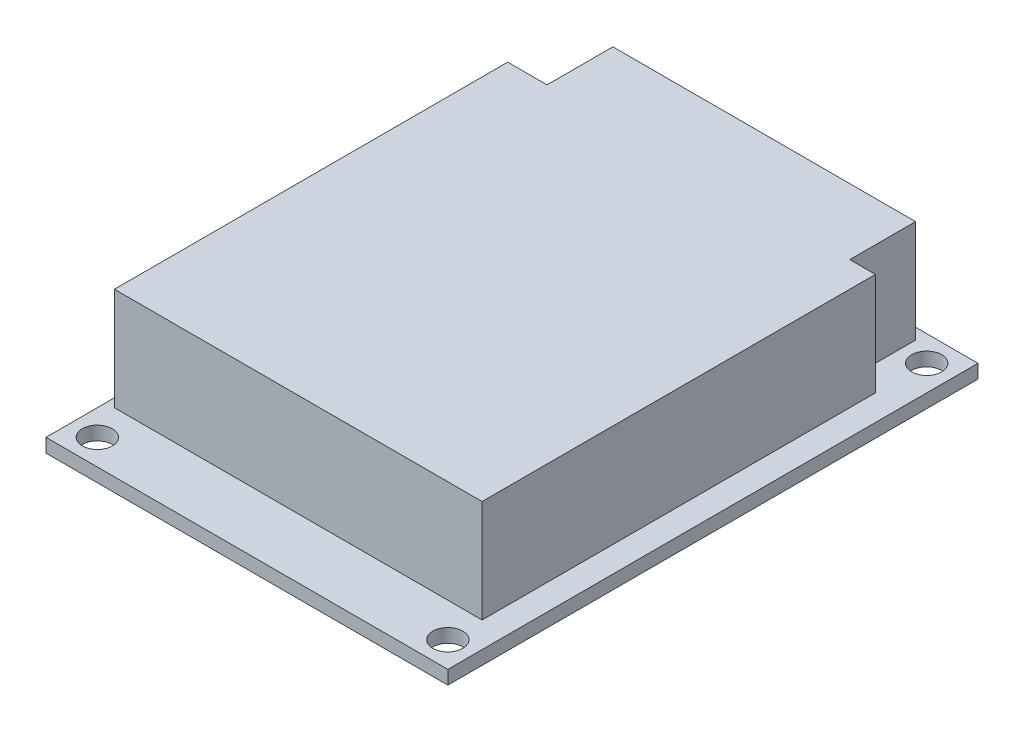
SolidWorks part; units mm, degrees
ref_plane "Front Plane" through (0, 0, 0) normal (0, 0, 1) x (1, 0, 0)
ref_plane "Top Plane" through (0, 0, 0) normal (0, 1, 0) x (1, 0, 0)
ref_plane "Right Plane" through (0, 0, 0) normal (1, 0, 0) x (0, 0, -1)
sketch "Sketch1" plane through (0, 0, 0) normal (0, 1, 0) x (1, 0, 0)
  line L5 (-23.5, -31) -> (23.5, -31)
  line L6 (-23.5, -31) -> (-23.5, 31)
  line L11 (-23.5, 31) -> (23.5, 31)
  line L13 (23.5, -31) -> (23.5, 31)
  line L14 (-23.5, -31) -> (23.5, 31) construction
  line L15 (-23.5, 31) -> (23.5, -31) construction
  circle A4 centre (-20.5, -28) radius 1.75
  circle A5 centre (20.5, -28) radius 1.75
  circle A6 centre (20.5, 28) radius 1.75
  circle A7 centre (-20.5, 28) radius 1.75
  point P0 (0, 0)
  dimension "D3" = 3.5
  dimension "D8" = 3.5
  dimension "D9" = 3.5
  dimension "D10" = 3.5
  dimension "D1" = 47
  dimension "D2" = 62
  dimension "D4" = 3
  dimension "D5" = 3
  dimension "D6" = 3
  dimension "D7" = 3
  dimension "D11" = 3
  dimension "D12" = 3
  dimension "D13" = 3
  dimension "D14" = 3
extrude "Boss-Extrude1" add sketch "Sketch1" against normal blind 1.6
sketch "Sketch3" plane through (0, 0, 0) normal (0, 1, 0) x (1, 0, 0)
  line L0 (-23.5, 31) -> (-23.5, -31) construction
  line L5 (-22.5, 22) -> (-17.9, 22)
  line L6 (-22.5, 22) -> (-22.5, -24)
  line L7 (-22.5, -24) -> (20.5, -24)
  line L8 (20.5, 22) -> (20.5, -24)
  line L11 (23.5, -31) -> (23.5, 31) construction
  line L12 (23.5, 31) -> (-23.5, 31) construction
  line L13 (-23.5, -31) -> (23.5, -31) construction
  line L14 (-23.5, -31) -> (-23.5, 31) construction
  line L16 (-17.9, 22) -> (-17.9, 29.7)
  line L17 (-17.9, 29.7) -> (17.5, 29.7)
  line L18 (17.5, 22) -> (17.5, 29.7)
  line L21 (-23.5, 31) -> (23.5, 31) construction
  line L22 (23.5, -31) -> (23.5, 31) construction
  line L25 (17.5, 22) -> (20.5, 22)
  point P13 (4.6594, 12.9808)
  point P16 (-7.4997, 0)
  dimension "D1" = 1
  dimension "D2" = 3
  dimension "D3" = 9
  dimension "D4" = 7
  dimension "D5" = 5.6
  dimension "D6" = 1.3
  dimension "D7" = 6
extrude "Boss-Extrude2" add sketch "Sketch3" along normal blind 12
